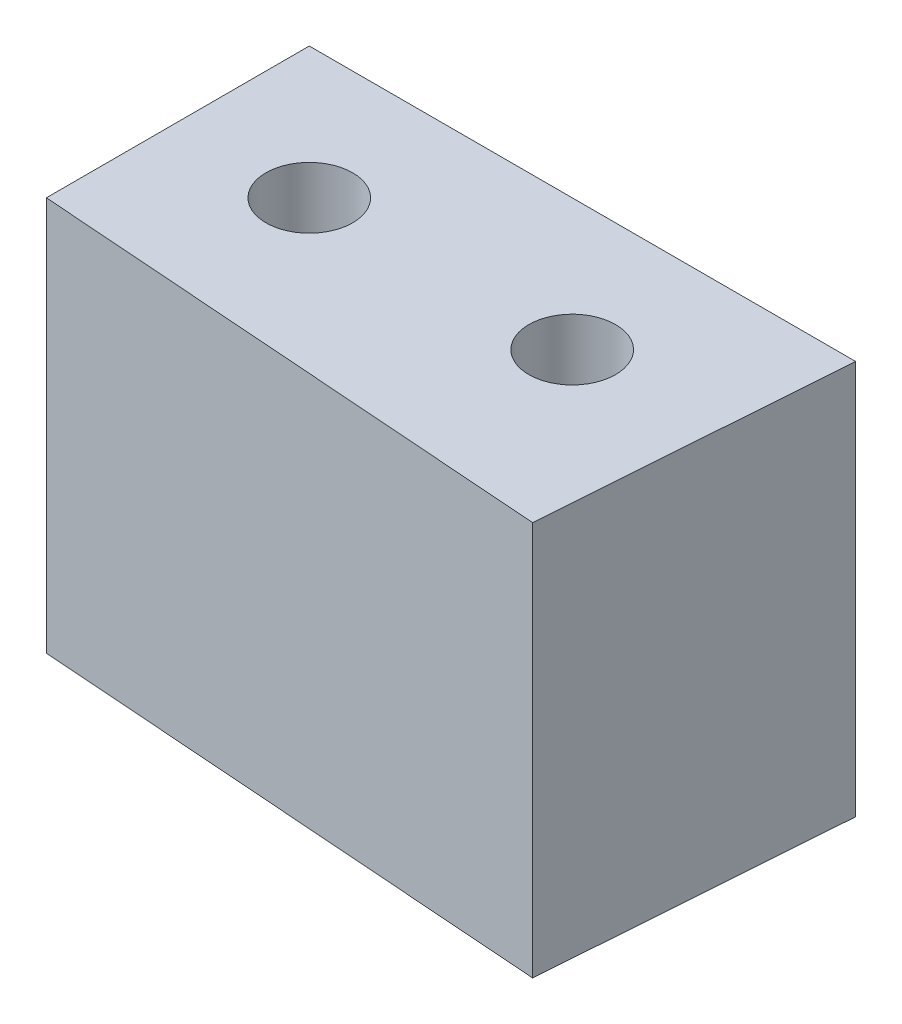
SolidWorks part; units mm, degrees
material "ABS"
ref_plane "前视基准面" through (0, 0, 0) normal (0, 0, 1) x (1, 0, 0)
ref_plane "上视基准面" through (0, 0, 0) normal (0, 1, 0) x (1, 0, 0)
ref_plane "右视基准面" through (0, 0, 0) normal (1, 0, 0) x (0, 0, -1)
other "Configuration Table"
sketch "草图1" plane through (0, 0, 0) normal (0, 1, 0) x (1, 0, 0)
  line L0 (0, -10) -> (-1.0892, -24.9604) construction
  line L1 (0, 0) -> (680, 0) construction
  line L2 (0, 0) -> (0, 15) construction
  line L3 (0, 15) -> (680, 15) construction
  line L4 (680, 0) -> (680, 15) construction
  line L5 (0, -10) -> (680, -59.51) construction
  line L6 (-1.0892, -24.9604) -> (678.9108, -74.4704) construction
  line L7 (680, -59.51) -> (678.9108, -74.4704) construction
  line L8 (0, 0) -> (0, -10)
  line L9 (0, -10) -> (19.9472, -11.4523) construction
  line L10 (19.9472, -11.4523) -> (20.781, 0)
  line L11 (20.781, 0) -> (0, 0) construction
  line L12 (654.2534, 0) -> (650.0792, -57.3315) construction
  line L13 (650.0792, -57.3315) -> (680, -59.51) construction
  line L14 (680, -59.51) -> (680, 0) construction
  line L15 (680, 0) -> (654.2534, 0) construction
  line L16 (570.2904, -51.5222) -> (571.6245, -33.1995) construction
  line L17 (570.2904, -51.5222) -> (-45.7125, -51.5222) construction
  line L18 (0, 0) -> (20.781, 0)
  line L19 (0, -10) -> (19.9472, -11.4523)
  dimension "D1" = 15
  dimension "D2" = 15
  dimension "D3" = 680
  dimension "D4" = 20
  dimension "D5" = 80
  dimension "D6" = 681.8
  dimension "D7" = 30
  dimension "D8" = 10
extrude "凸台-拉伸1" add sketch "草图1" along normal blind 15
sketch "草图2" plane through (0, 0, 0) normal (0, -1, 0) x (1, 0, 0)
  circle A0 centre (5, 5) radius 1.45 construction
  circle A1 centre (15, 5) radius 1.45 construction
  circle A2 centre (5, 5) radius 1.45
  circle A3 centre (15, 5) radius 1.45
extrude "切除-拉伸1" cut sketch "草图2" against normal through all
sketch "草图3" plane through (0, 0, 0) normal (0, -1, 0) x (1, 0, 0)
  circle A0 centre (5, 5) radius 1.65
  circle A1 centre (15, 5) radius 1.65
  circle A2 centre (5, 5) radius 1.45 construction
  circle A5 centre (15, 5) radius 1.45 construction
  dimension "D1" = 3.3
  dimension "D2" = 3.3
extrude "切除-拉伸2" cut sketch "草图3" against normal through all
